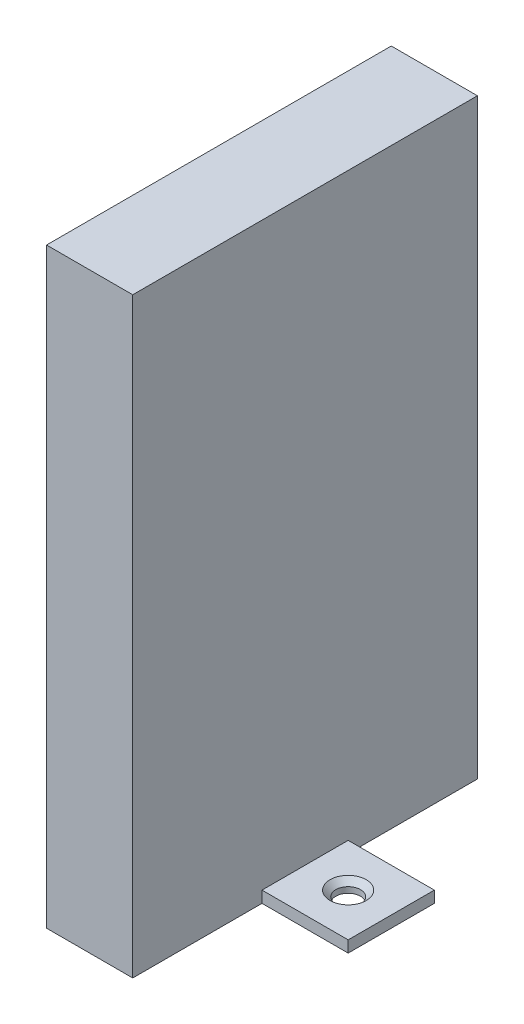
SolidWorks part; units mm, degrees
ref_plane "Front Plane" through (0, 0, 0) normal (0, 0, 1) x (1, 0, 0)
ref_plane "Top Plane" through (0, 0, 0) normal (0, 1, 0) x (1, 0, 0)
ref_plane "Right Plane" through (0, 0, 0) normal (1, 0, 0) x (0, 0, -1)
sketch "Sketch1" plane through (0, 0, 0) normal (0, 1, 0) x (1, 0, 0)
  line L0 (0, 0) -> (0, 60)
  line L1 (0, 60) -> (15, 60)
  line L2 (15, 60) -> (15, 0)
  line L3 (15, 0) -> (0, 0)
  dimension "D1" = 15
  dimension "D2" = 60
extrude "Boss-Extrude1" add sketch "Sketch1" along normal blind 103
sketch "Sketch2" plane through (15, 0, 0) normal (1, 0, 0) x (0, 0, -1)
  line L0 (22.5, 0) -> (22.5, 2)
  line L1 (0, 0) -> (60, 0) construction
  line L2 (22.5, 2) -> (37.5, 2)
  line L3 (37.5, 2) -> (37.5, 0)
  line L4 (37.5, 0) -> (22.5, 0)
  line L5 (60, 103) -> (60, 0) construction
  dimension "D1" = 15
  dimension "D2" = 22.5
  dimension "D3" = 2
extrude "Boss-Extrude2" add sketch "Sketch2" along normal blind 15
sketch "Sketch3" plane through (0, 0, 0) normal (-1, 0, 0) x (0, 0, 1)
  line L0 (-37.5, 0) -> (-37.5, 2)
  line L1 (-60, 0) -> (0, 0) construction
  line L2 (-37.5, 2) -> (-22.5, 2)
  line L3 (-22.5, 2) -> (-22.5, 0)
  line L4 (-22.5, 0) -> (-37.5, 0)
  line L5 (-60, 103) -> (-60, 0) construction
  dimension "D1" = 15
  dimension "D2" = 2
  dimension "D3" = 22.5
extrude "Boss-Extrude3" add sketch "Sketch3" along normal blind 15
sketch "Sketch4" plane through (0, 2, 0) normal (0, 1, 0) x (1, 0, 0)
  line L0 (30, 22.5) -> (15, 22.5) construction
  line L1 (30, 37.5) -> (30, 22.5) construction
  line L2 (-15, 22.5) -> (-15, 37.5) construction
  line L3 (-15, 22.5) -> (0, 22.5) construction
  circle A0 centre (22.5, 30) radius 2.15
  circle A1 centre (-7.5, 30) radius 2.15
  dimension "D1" = 4.3
  dimension "D2" = 4.3
  dimension "D3" = 7.5
  dimension "D4" = 7.5
  dimension "D5" = 7.5
  dimension "D6" = 7.5
extrude "Cut-Extrude1" cut sketch "Sketch4" against normal blind 15
chamfer "Chamfer2" distance 1 angle 45 2 edges at (22.5, 2, -27.85) (-7.5, 2, -27.85)
